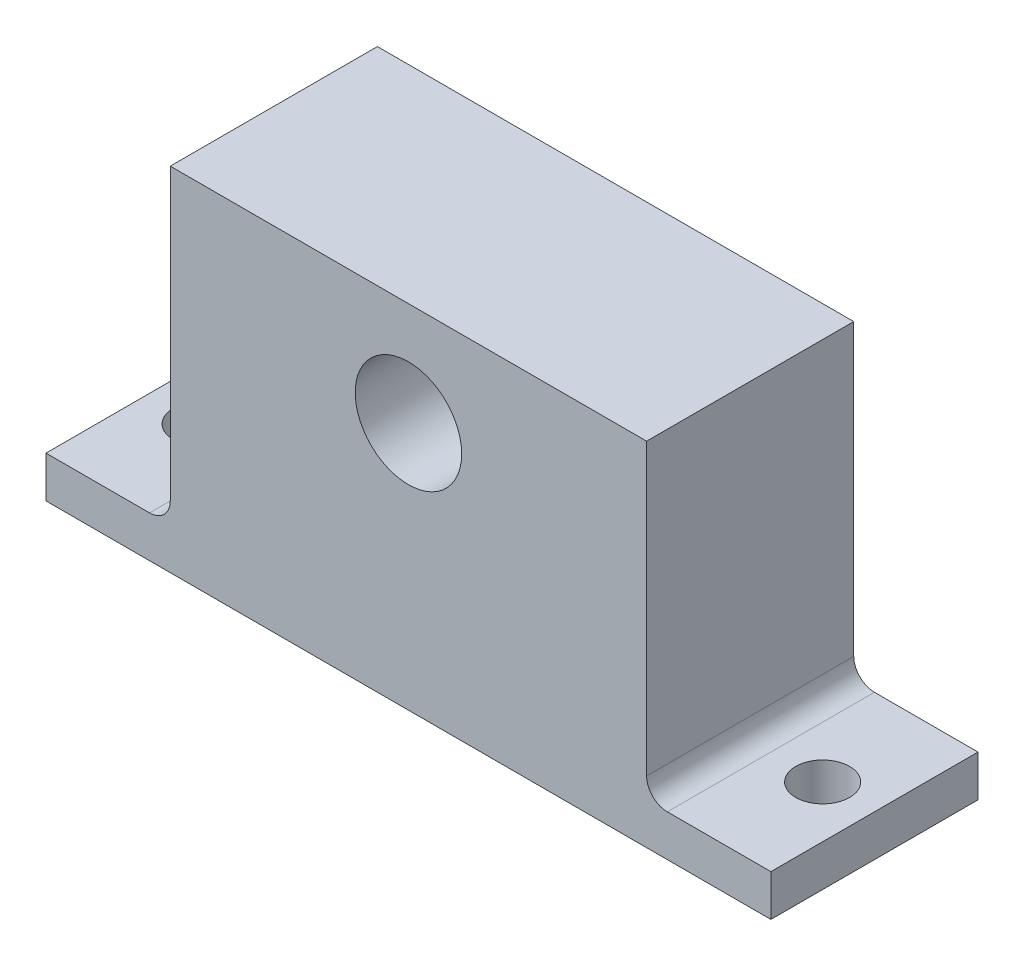
SolidWorks part; units mm, degrees
material "ABS"
ref_plane "Front Plane" through (0, 0, 0) normal (0, 0, 1) x (1, 0, 0)
ref_plane "Top Plane" through (0, 0, 0) normal (0, 1, 0) x (1, 0, 0)
ref_plane "Right Plane" through (0, 0, 0) normal (1, 0, 0) x (0, 0, -1)
sketch "Sketch1" plane through (0, 0, 0) normal (0, 0, 1) x (1, 0, 0)
  line L1 (-22.225, -10.795) -> (22.225, -10.795)
  line L2 (-22.225, -10.795) -> (-22.225, 10.795)
  line L3 (-22.225, 10.795) -> (22.225, 10.795)
  line L4 (22.225, -10.795) -> (22.225, 10.795)
  line L5 (-22.225, -10.795) -> (22.225, 10.795) construction
  line L6 (-22.225, 10.795) -> (22.225, -10.795) construction
  point P0 (0, 0)
  dimension "D1" = 44.45
  dimension "D2" = 21.59
extrude "Boss-Extrude1" add sketch "Sketch1" along normal blind 12.7
sketch "Sketch2" plane through (0, 0, 12.7) normal (0, 0, 1) x (1, 0, 0)
  line L0 (-22.225, -10.795) -> (22.225, -10.795) construction
  line L1 (-22.225, 10.795) -> (-14.605, 10.795)
  line L2 (-22.225, 10.795) -> (-22.225, -8.255)
  line L3 (-22.225, -8.255) -> (-14.605, -8.255)
  line L4 (-14.605, 10.795) -> (-14.605, -8.255)
  line L5 (22.225, 10.795) -> (14.605, 10.795)
  line L6 (22.225, 10.795) -> (22.225, -8.255)
  line L7 (22.225, -8.255) -> (14.605, -8.255)
  line L8 (14.605, 10.795) -> (14.605, -8.255)
  dimension "D1" = 7.62
  dimension "D2" = 7.62
  dimension "D3" = 2.54
  dimension "D4" = 2.54
extrude "Cut-Extrude1" cut sketch "Sketch2" against normal blind 12.7
fillet "Fillet1" radius 1.27 1 edges at (-14.605, -8.255, 6.35)
fillet "Fillet2" radius 1.27 1 edges at (14.605, -8.255, 6.35)
sketch "Sketch4" plane through (0, -8.255, 0) normal (0, 1, 0) x (1, 0, 0)
  line L0 (22.225, 0) -> (22.225, -12.7) construction
  line L1 (15.875, 0) -> (22.225, 0) construction
  line L2 (-22.225, 0) -> (-15.875, 0) construction
  line L3 (-22.225, 0) -> (-22.225, -12.7) construction
  circle A0 centre (19.05, -6.35) radius 1.651
  circle A1 centre (-19.05, -6.4262) radius 1.651
  dimension "D1" = 3.302
  dimension "D2" = 3.302
  dimension "D3" = 3.175
  dimension "D4" = 6.35
  dimension "D5" = 6.4262
  dimension "D6" = 3.175
extrude "Cut-Extrude3" cut sketch "Sketch4" against normal blind 12.7
sketch "Sketch5" plane through (0, 0, 0) normal (0, 0, -1) x (-1, 0, 0)
  line L0 (-14.605, 10.795) -> (14.605, 10.795) construction
  circle A0 centre (0, 4.445) radius 1.8034
  dimension "D1" = 3.6068
  dimension "D2" = 6.35
extrude "Cut-Extrude4" cut sketch "Sketch5" against normal blind 12.7
sketch "Sketch6" plane through (0, 0, 12.7) normal (0, 0, 1) x (1, 0, 0)
  circle A0 centre (0, 4.445) radius 3.2639
  dimension "D1" = 6.5278
extrude "Cut-Extrude5" cut sketch "Sketch6" against normal blind 5.08 contours A0
